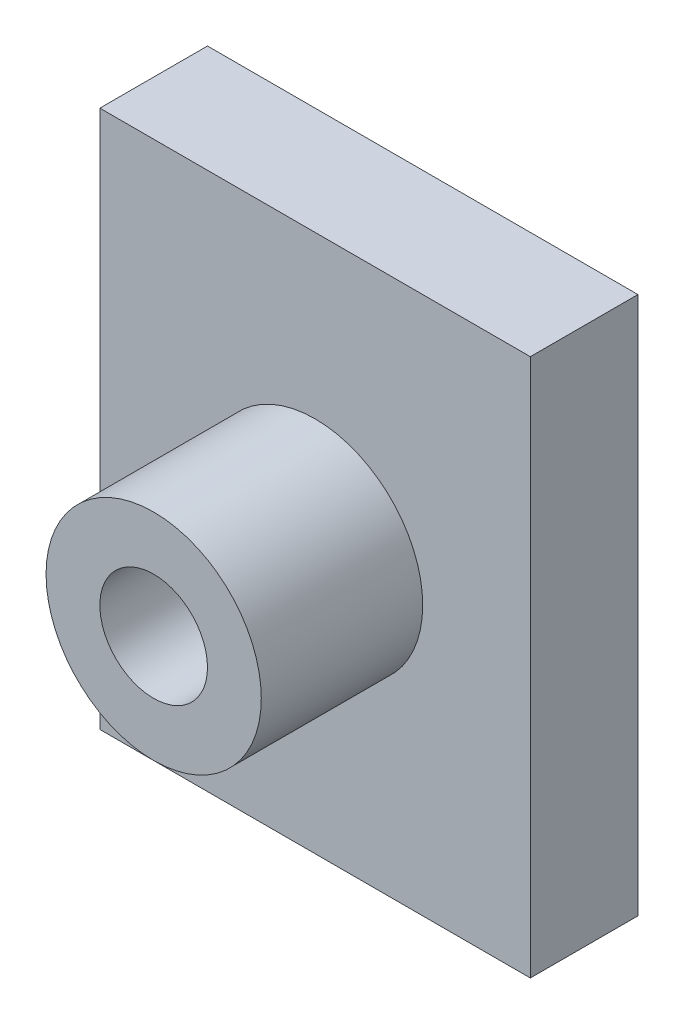
SolidWorks part; units mm, degrees
ref_plane "Plan de face" through (0, 0, 0) normal (0, 0, 1) x (1, 0, 0)
ref_plane "Plan de dessus" through (0, 0, 0) normal (0, 1, 0) x (1, 0, 0)
ref_plane "Plan de droite" through (0, 0, 0) normal (1, 0, 0) x (0, 0, -1)
sketch "Esquisse1" plane through (0, 0, 0) normal (0, 0, 1) x (1, 0, 0)
  line L0 (-40, 50) -> (40, -50) construction
  line L1 (-40, 50) -> (40, 50)
  line L2 (-40, 50) -> (-40, -50)
  line L3 (-40, -50) -> (40, -50)
  line L4 (40, 50) -> (40, -50)
  dimension "D1" = 80
  dimension "D2" = 100
extrude "Boss.-Extru.1" add sketch "Esquisse1" along normal blind 20
sketch "Esquisse2" plane through (0, 0, 20) normal (0, 0, 1) x (1, 0, 0)
  circle A0 centre (0, 0) radius 20
  dimension "D1" = 40
extrude "Boss.-Extru.2" add sketch "Esquisse2" along normal blind 30
sketch "Esquisse3" plane through (0, 0, 50) normal (0, 0, 1) x (1, 0, 0)
  circle A0 centre (0, 0) radius 10
  dimension "D1" = 20
extrude "Enlèv. mat.-Extru.1" cut sketch "Esquisse3" against normal through all
